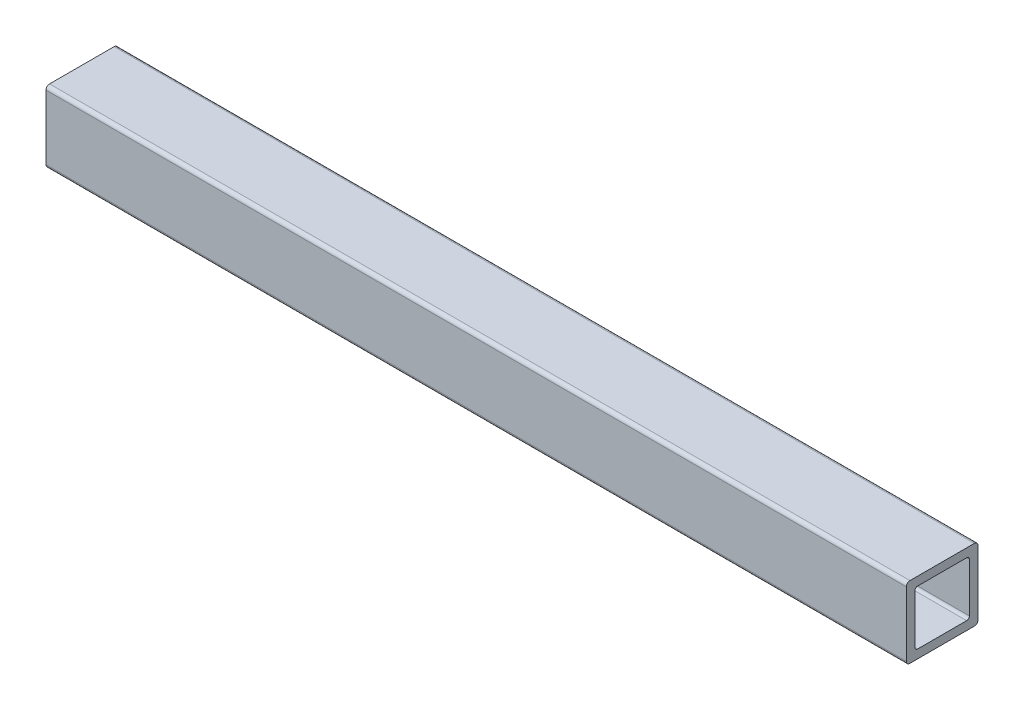
SolidWorks part; units mm, degrees
ref_plane "Front" through (0, 0, 0) normal (0, 0, 1) x (1, 0, 0)
ref_plane "Top" through (0, 0, 0) normal (0, 1, 0) x (1, 0, 0)
ref_plane "Right" through (0, 0, 0) normal (1, 0, 0) x (0, 0, -1)
sketch "Sketch1" plane through (0, 0, 0) normal (1, 0, 0) x (0, 0, -1)
  line L0 (-9.652, 0) -> (-12.7, 0) construction
  line L1 (11.43, -12.7) -> (-11.43, -12.7) construction
  line L2 (12.7, -11.43) -> (12.7, 11.43) construction
  line L3 (11.43, 12.7) -> (-11.43, 12.7) construction
  line L4 (-12.7, -11.43) -> (-12.7, 11.43) construction
  line L5 (12.7, -12.7) -> (-12.7, 12.7) construction
  line L6 (12.7, 12.7) -> (-12.7, -12.7) construction
  line L7 (8.6868, 9.652) -> (-8.6868, 9.652) construction
  line L8 (9.652, 8.6868) -> (9.652, -8.6868) construction
  line L9 (8.6868, -9.652) -> (-8.6868, -9.652) construction
  line L10 (-9.652, 8.6868) -> (-9.652, -8.6868) construction
  line L11 (9.652, 9.652) -> (-9.652, -9.652) construction
  line L12 (9.652, -9.652) -> (-9.652, 9.652) construction
  line L13 (0, -9.652) -> (0, -12.7) construction
  line L14 (9.652, -8.6868) -> (9.652, -12.7) construction
  line L15 (9.652, 0) -> (12.7, 0) construction
  line L16 (9.652, -12.7) -> (12.7, -12.7) construction
  arc A0 (-8.6868, -9.652) -> (-9.652, -8.6868) centre (-8.6868, -8.6868) cw construction
  arc A1 (9.652, -8.6868) -> (8.6868, -9.652) centre (8.6868, -8.6868) cw construction
  arc A2 (8.6868, 9.652) -> (9.652, 8.6868) centre (8.6868, 8.6868) cw construction
  arc A3 (-8.6868, 9.652) -> (-9.652, 8.6868) centre (-8.6868, 8.6868) ccw construction
  arc A4 (11.43, -12.7) -> (12.7, -11.43) centre (11.43, -11.43) ccw construction
  arc A5 (12.7, 11.43) -> (11.43, 12.7) centre (11.43, 11.43) ccw construction
  arc A6 (-11.43, 12.7) -> (-12.7, 11.43) centre (-11.43, 11.43) ccw construction
  arc A7 (-11.43, -12.7) -> (-12.7, -11.43) centre (-11.43, -11.43) cw construction
  point P0 (0, 0)
  point P6 (0, 0)
  dimension "D2" = 0.9652
  dimension "D3" = 1.27
  dimension "Outside Width" = 25.4
  dimension "Ouside Height" = 25.4
  dimension "Inside Height" = 19.304
  dimension "Wall Thickness" = 3.048
sketch "Sketch2" plane through (0, 0, 0) normal (0, 0, 1) x (1, 0, 0)
  line L0 (-152.4, 0) -> (152.4, 0) construction
  point P3 (-130.048, 0)
  point P4 (130.048, 0)
  dimension "Length" = 304.8
  dimension "D1" = 22.352
  dimension "D2" = 22.352
sketch "Sketch4" plane through (0, 0, 0) normal (1, 0, 0) x (0, 0, -1)
  line L8 (12.7, -11.43) -> (12.7, 11.43)
  line L9 (11.43, 12.7) -> (-11.43, 12.7)
  line L10 (-12.7, -11.43) -> (-12.7, 11.43)
  line L11 (11.43, -12.7) -> (-11.43, -12.7)
  line L12 (9.652, 8.6868) -> (9.652, -8.6868)
  line L13 (8.6868, -9.652) -> (-8.6868, -9.652)
  line L14 (-9.652, 8.6868) -> (-9.652, -8.6868)
  line L15 (8.6868, 9.652) -> (-8.6868, 9.652)
  arc A8 (12.7, 11.43) -> (11.43, 12.7) centre (11.43, 11.43) ccw
  arc A9 (-11.43, 12.7) -> (-12.7, 11.43) centre (-11.43, 11.43) ccw
  arc A10 (-12.7, -11.43) -> (-11.43, -12.7) centre (-11.43, -11.43) ccw
  arc A11 (11.43, -12.7) -> (12.7, -11.43) centre (11.43, -11.43) ccw
  arc A12 (8.6868, -9.652) -> (9.652, -8.6868) centre (8.6868, -8.6868) ccw
  arc A13 (-9.652, -8.6868) -> (-8.6868, -9.652) centre (-8.6868, -8.6868) ccw
  arc A14 (-8.6868, 9.652) -> (-9.652, 8.6868) centre (-8.6868, 8.6868) ccw
  arc A15 (9.652, 8.6868) -> (8.6868, 9.652) centre (8.6868, 8.6868) ccw
extrude "Boss-Extrude1" add sketch "Sketch4" along normal up to vertex (152.4 mm away) and the other way up to vertex (152.4 mm away)
equation "\"D3@Sketch1\"=\"Outside Width@Sketch1\"*.05"
equation "\"D2@Sketch1\" = \"Inside Height@Sketch1\" * .05"
equation "\"D1@Sketch2\"=\"Outside Width@Sketch1\"-\"Wall Thickness@Sketch1\""
equation "\"D2@Sketch2\"=\"D1@Sketch2\""
